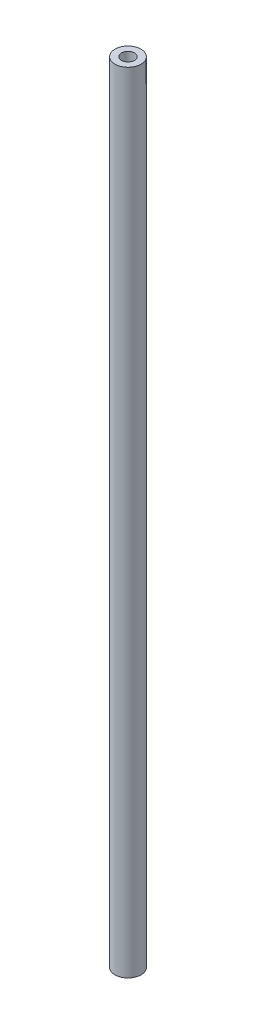
SolidWorks part; units mm, degrees
ref_plane "Front Plane" through (0, 0, 0) normal (0, 0, 1) x (1, 0, 0)
ref_plane "Top Plane" through (0, 0, 0) normal (0, 1, 0) x (1, 0, 0)
ref_plane "Right Plane" through (0, 0, 0) normal (1, 0, 0) x (0, 0, -1)
sketch "Sketch1" plane through (0, 0, 0) normal (0, 1, 0) x (1, 0, 0)
  circle A0 centre (0, 0) radius 6.35
  circle A1 centre (0, 0) radius 3.175
  dimension "D1" = 12.7
  dimension "D2" = 6.35
extrude "Boss-Extrude1" add sketch "Sketch1" along normal blind 384.302
equation "\"cm\"=10"
